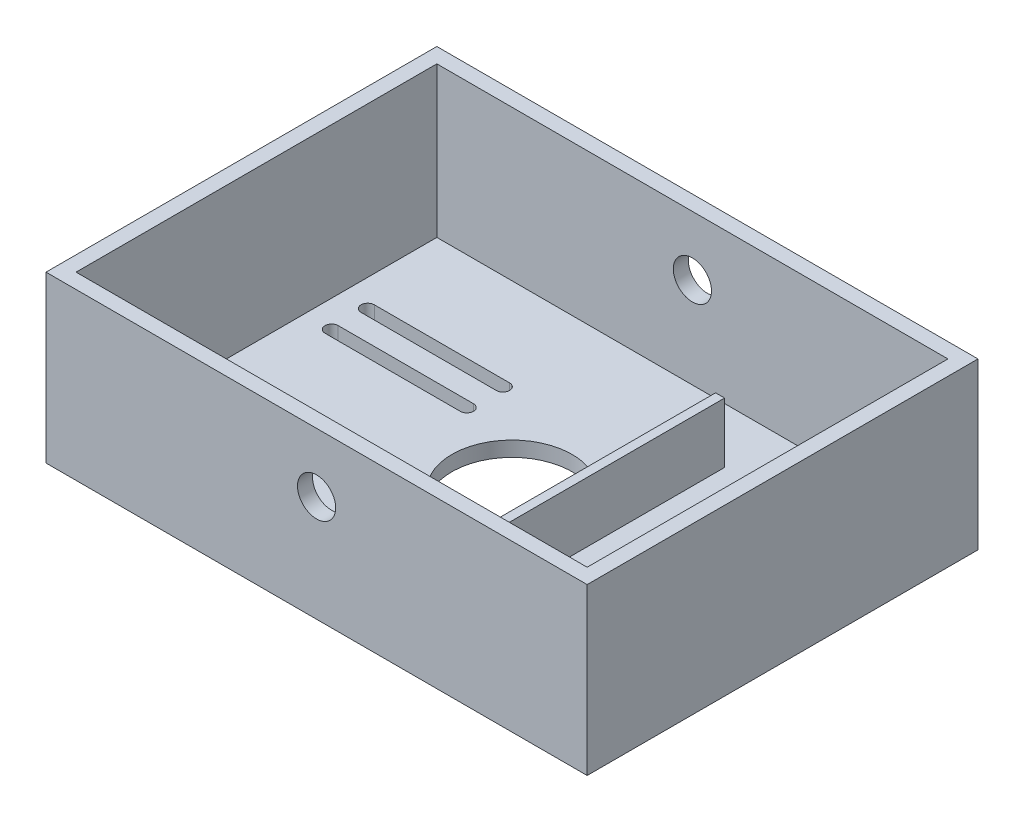
SolidWorks part; units mm, degrees
ref_plane "Plan de face" through (0, 0, 0) normal (0, 0, 1) x (1, 0, 0)
ref_plane "Plan de dessus" through (0, 0, 0) normal (0, 1, 0) x (1, 0, 0)
ref_plane "Plan de droite" through (0, 0, 0) normal (1, 0, 0) x (0, 0, -1)
sketch "Esquisse1" plane through (0, 0, 0) normal (0, 1, 0) x (1, 0, 0)
  line L1 (85, -60) -> (-85, -60)
  line L2 (85, -60) -> (85, 60)
  line L3 (85, 60) -> (-85, 60)
  line L4 (-85, -60) -> (-85, 60)
  line L5 (85, -60) -> (-85, 60) construction
  line L6 (85, 60) -> (-85, -60) construction
  line L7 (-90, -65) -> (90, -65)
  line L8 (-90, -65) -> (-90, 65)
  line L9 (-90, 65) -> (90, 65)
  line L10 (90, -65) -> (90, 65)
  line L11 (-90, -65) -> (90, 65) construction
  line L12 (-90, 65) -> (90, -65) construction
  point P0 (0, 0)
  point P5 (0, 0)
  dimension "D1" = 120
  dimension "D2" = 170
  dimension "D3" = 5
  dimension "D4" = 5
extrude "Boss.-Extru.2" add sketch "Esquisse1" along normal blind 55
sketch "Esquisse2" plane through (0, 0, 0) normal (0, 1, 0) x (1, 0, 0)
  line L1 (-85, 60) -> (85, 60)
  line L2 (-85, 60) -> (-85, -60)
  line L3 (-85, -60) -> (85, -60)
  line L4 (85, 60) -> (85, -60)
extrude "Boss.-Extru.3" add sketch "Esquisse2" along normal blind 5
sketch "Esquisse3" plane through (0, 5, 0) normal (0, 1, 0) x (1, 0, 0)
  circle A0 centre (0, 0) radius 20
  dimension "D1" = 40
extrude "Enlèv. mat.-Extru.1" cut sketch "Esquisse3" against normal through all
sketch "Esquisse4" plane through (0, 5, 0) normal (0, 1, 0) x (1, 0, 0)
  line L1 (85, 60) -> (-85, 60) construction
  line L2 (0, 60) -> (0, -60) construction
  line L3 (-85, -60) -> (85, -60) construction
  line L5 (-76, 28) -> (-31, 28) construction
  line L6 (-76, 30.2) -> (-31, 30.2)
  line L7 (-76, 25.8) -> (-31, 25.8)
  line L8 (-76, 16) -> (-31, 16) construction
  line L9 (-76, 18.2) -> (-31, 18.2)
  line L10 (-76, 13.8) -> (-31, 13.8)
  line L11 (-85, 60) -> (-85, -60) construction
  arc A0 (-76, 30.2) -> (-76, 25.8) centre (-76, 28) ccw
  arc A1 (-31, 25.8) -> (-31, 30.2) centre (-31, 28) ccw
  arc A2 (-76, 18.2) -> (-76, 13.8) centre (-76, 16) ccw
  arc A3 (-31, 13.8) -> (-31, 18.2) centre (-31, 16) ccw
  point P0 (0, 0)
  point P5 (0, 0)
  point P14 (-53.5, 28)
  point P21 (-53.5, 16)
  point P26 (-27.9993, -7.1306)
  point P27 (-28.2089, -4.0308)
  point P28 (0, 0)
  point P29 (0, 0)
  point P30 (-59.821, 5.8)
  point P31 (-66.5978, 5.8)
  dimension "D1" = 2.2
  dimension "D2" = 45
  dimension "D3" = 12
  dimension "D4" = 9
  dimension "D5" = 32
extrude "Enlèv. mat.-Extru.2" cut sketch "Esquisse4" against normal through all
sketch "Esquisse5" plane through (0, 0, -65) normal (0, 0, -1) x (-1, 0, 0)
  line L3 (0, 55) -> (0, 0) construction
  line L4 (-90, 55) -> (90, 55) construction
  line L5 (-90, 0) -> (90, 0) construction
  circle A0 centre (0, 35.25) radius 6.35
  dimension "D1" = 12.7
  dimension "D2" = 35.25
extrude "Enlèv. mat.-Extru.3" cut sketch "Esquisse5" against normal up to surface (130 mm away) up to face at (0, 27.5, 65)
sketch "Esquisse6" plane through (0, 5, 0) normal (0, 1, 0) x (1, 0, 0)
  line L1 (26.12, 41.6) -> (29.12, 41.6)
  line L2 (26.12, 41.6) -> (26.12, -60)
  line L3 (26.12, -60) -> (29.12, -60)
  line L4 (29.12, 41.6) -> (29.12, -60)
  line L10 (85, -60) -> (85, 60) construction
  line L11 (85, -60) -> (-85, -60) construction
  dimension "D1" = 3
  dimension "D2" = 101.6
  dimension "D3" = 55.88
extrude "Boss.-Extru.4" add sketch "Esquisse6" along normal blind 20
